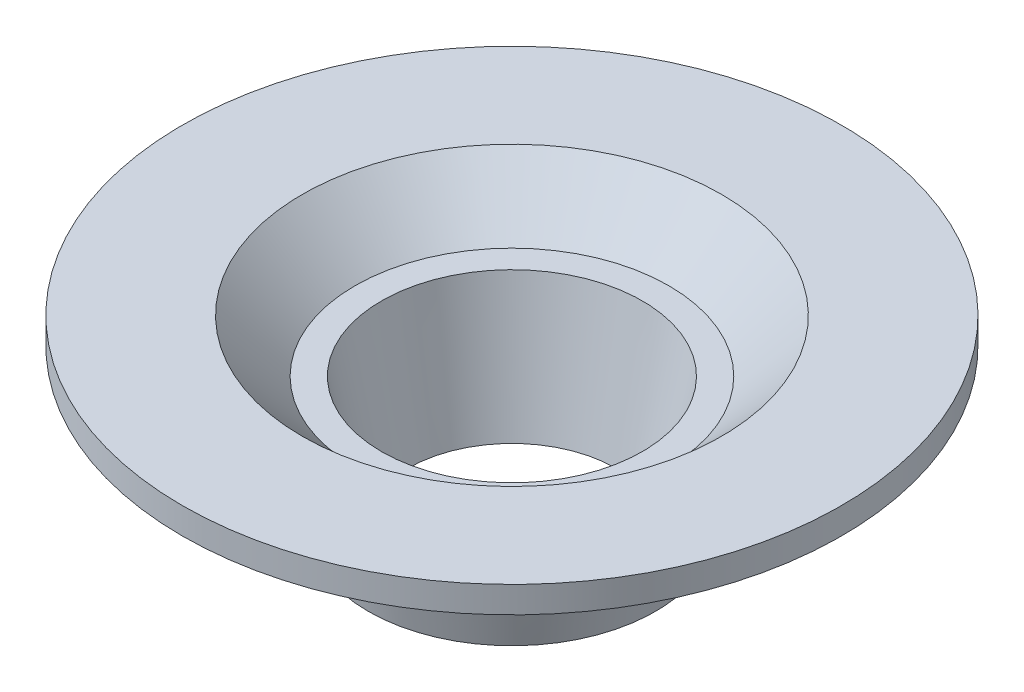
SolidWorks part; units mm, degrees
ref_plane "Front Plane" through (0, 0, 0) normal (0, 0, 1) x (1, 0, 0)
ref_plane "Top Plane" through (0, 0, 0) normal (0, 1, 0) x (1, 0, 0)
ref_plane "Right Plane" through (0, 0, 0) normal (1, 0, 0) x (0, 0, -1)
sketch "Sketch1" plane through (0, 0, 0) normal (0, 0, 1) x (1, 0, 0)
  line L0 (0, 0) -> (0, -5) construction
  line L1 (4.95, 0) -> (5.95, 0)
  line L2 (5.95, 0) -> (7.95, 2)
  line L3 (7.95, 2) -> (12.5, 2)
  line L5 (10.5, 1) -> (8.5, -1)
  line L6 (8.5, -1) -> (6.25, -1)
  line L7 (6.25, -1) -> (5.45, -5)
  line L8 (5.45, -5) -> (3.95, -5)
  line L9 (3.95, -5) -> (4.95, 0)
  line L10 (10.5, 1) -> (12.5, 1)
  line L11 (12.5, 1) -> (12.5, 2)
  point P5 (10.2705, 4.6455)
  point P7 (5.7556, 0)
  dimension "D1" = 5
  dimension "D2" = 7.9
  dimension "D3" = 25
  dimension "D4" = 2
  dimension "D5" = 2
  dimension "D6" = 1
  dimension "D7" = 2
  dimension "D8" = 4
  dimension "D9" = 12.5
  dimension "D10" = 1.5
  dimension "D11" = 9.9
  dimension "D12" = 1
revolve "Revolve1" add sketch "Sketch1" angle 360 about L0
